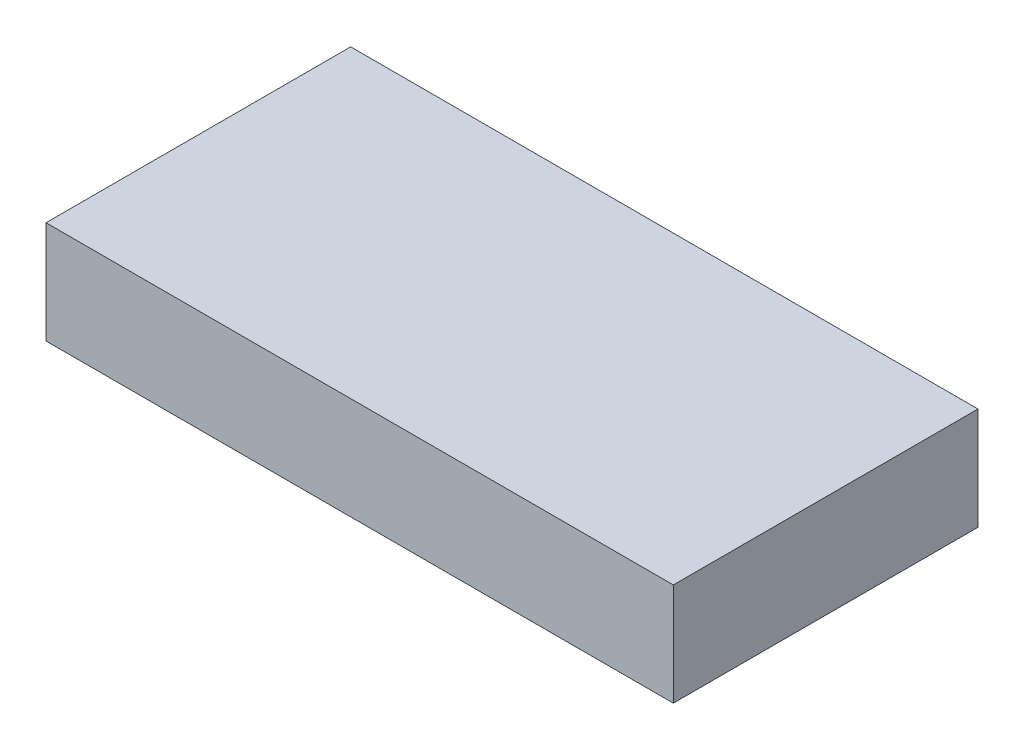
SolidWorks part; units mm, degrees
ref_plane "Front Plane" through (0, 0, 0) normal (0, 0, 1) x (1, 0, 0)
ref_plane "Top Plane" through (0, 0, 0) normal (0, 1, 0) x (1, 0, 0)
ref_plane "Right Plane" through (0, 0, 0) normal (1, 0, 0) x (0, 0, -1)
sketch "Sketch1" plane through (0, 0, 0) normal (0, 1, 0) x (1, 0, 0)
  line L1 (0, 0) -> (245, 0)
  line L2 (0, 0) -> (0, 119)
  line L3 (0, 119) -> (245, 119)
  line L4 (245, 0) -> (245, 119)
  dimension "D1" = 119
  dimension "D2" = 245
extrude "Boss-Extrude1" add sketch "Sketch1" along normal blind 40
